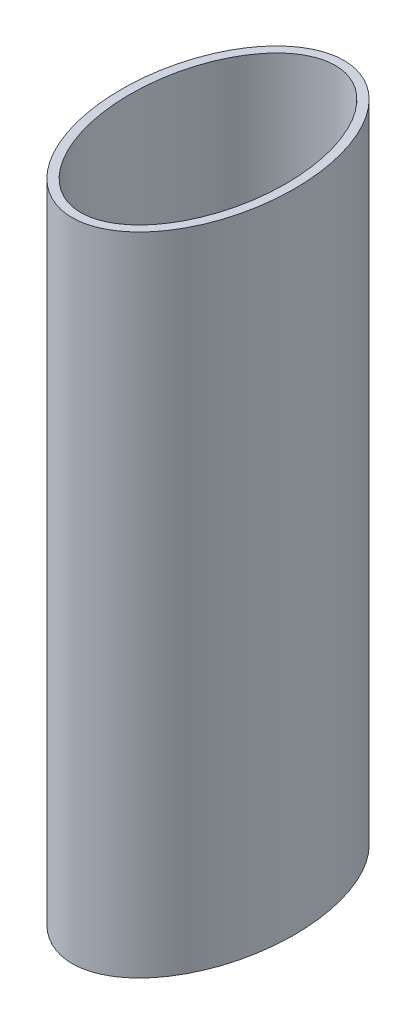
SolidWorks part; units mm, degrees
ref_plane "Front Plane" through (0, 0, 0) normal (0, 0, 1) x (1, 0, 0)
ref_plane "Top Plane" through (0, 0, 0) normal (0, 1, 0) x (1, 0, 0)
ref_plane "Right Plane" through (0, 0, 0) normal (1, 0, 0) x (0, 0, -1)
sketch "Sketch1" plane through (0, 0, 0) normal (0, 1, 0) x (1, 0, 0)
  ellipse E0 centre (0, 0) end of major axis (0, 40.005) minor radius 25.4
  dimension "D1" = 40.005
  dimension "D2" = 25.4
extrude "Boss-Extrude1" add sketch "Sketch1" along normal blind 190
shell "Shell1" thickness 2.54
